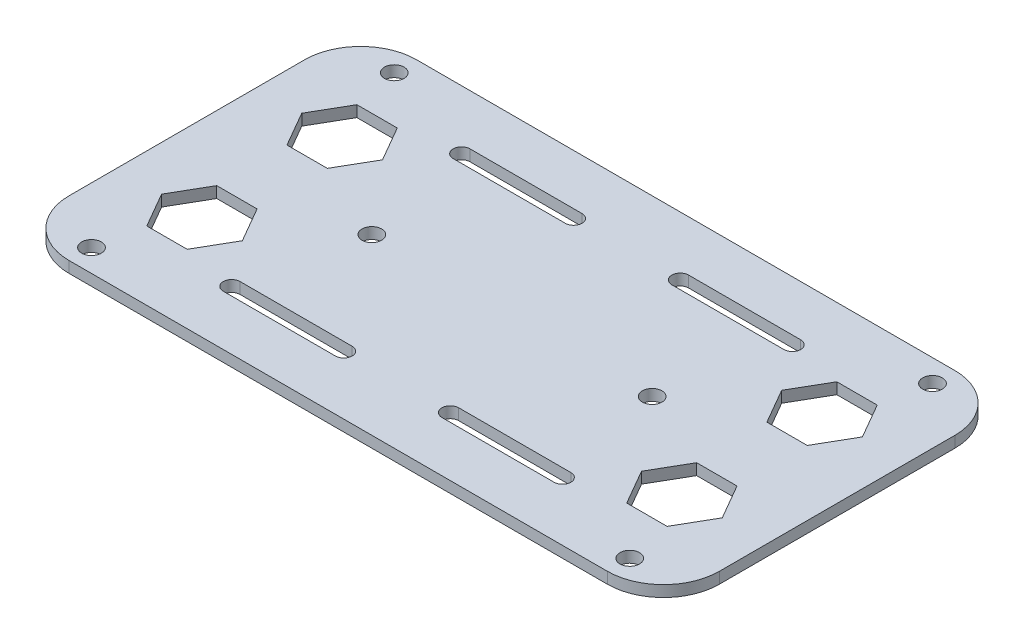
SolidWorks part; units mm, degrees
material "Thornel Mat VMA"
ref_plane "Front Plane" through (0, 0, 0) normal (0, 0, 1) x (1, 0, 0)
ref_plane "Top Plane" through (0, 0, 0) normal (0, 1, 0) x (1, 0, 0)
ref_plane "Right Plane" through (0, 0, 0) normal (1, 0, 0) x (0, 0, -1)
sketch "Sketch1" plane through (0, 0, 0) normal (0, 1, 0) x (1, 0, 0)
  line L1 (-58, 31) -> (58, 31)
  line L2 (-58, 31) -> (-58, -31)
  line L3 (-58, -31) -> (58, -31)
  line L4 (58, 31) -> (58, -31)
  line L5 (-58, 31) -> (58, -31) construction
  line L6 (-58, -31) -> (58, 31) construction
  point P0 (0, 0)
  dimension "D1" = 62
  dimension "D2" = 116
extrude "Boss-Extrude1" add sketch "Sketch1" along normal blind 2
sketch "Sketch2" plane through (0, 2, 0) normal (0, 1, 0) x (1, 0, 0)
  circle A0 centre (-48, 27) radius 1.75
  circle A1 centre (48, 27) radius 1.75
  circle A2 centre (48, -27) radius 1.75
  circle A3 centre (-48, -27) radius 1.75
  dimension "D1" = 3.5
  dimension "D2" = 48
  dimension "D3" = 27
  dimension "D4" = 96
  dimension "D5" = 54
extrude "Cut-Extrude1" cut sketch "Sketch2" against normal blind 2
sketch "Sketch3" plane through (0, 2, 0) normal (0, 1, 0) x (1, 0, 0)
  line L0 (9.5, -20.5) -> (29.5, -20.5) construction
  line L1 (9.5, -19) -> (29.5, -19)
  line L2 (9.5, -22) -> (29.5, -22)
  line L3 (-58, -31) -> (58, -31) construction
  line L4 (-9.5, -20.5) -> (-29.5, -20.5) construction
  line L5 (-9.5, -22) -> (-29.5, -22)
  line L6 (-9.5, -19) -> (-29.5, -19)
  line L7 (-29.5, 20.5) -> (-9.5, 20.5) construction
  line L8 (-29.5, 22) -> (-9.5, 22)
  line L9 (-29.5, 19) -> (-9.5, 19)
  line L10 (9.5, 20.5) -> (29.5, 20.5) construction
  line L11 (9.5, 22) -> (29.5, 22)
  line L12 (9.5, 19) -> (29.5, 19)
  line L13 (58, 31) -> (-58, 31) construction
  line L27 (-35.6, 12.5) -> (-39.2, 18.7354)
  line L28 (-39.2, 18.7354) -> (-46.4, 18.7354)
  line L29 (-46.4, 18.7354) -> (-50, 12.5)
  line L30 (-50, 12.5) -> (-46.4, 6.2646)
  line L31 (-46.4, 6.2646) -> (-39.2, 6.2646)
  line L32 (-39.2, 6.2646) -> (-35.6, 12.5)
  line L33 (-35.6, -12.5) -> (-39.2, -6.2646)
  line L34 (-39.2, -6.2646) -> (-46.4, -6.2646)
  line L35 (-46.4, -6.2646) -> (-50, -12.5)
  line L36 (-50, -12.5) -> (-46.4, -18.7354)
  line L37 (-46.4, -18.7354) -> (-39.2, -18.7354)
  line L38 (-39.2, -18.7354) -> (-35.6, -12.5)
  line L39 (50, 12.5) -> (46.4, 18.7354)
  line L40 (46.4, 18.7354) -> (39.2, 18.7354)
  line L41 (39.2, 18.7354) -> (35.6, 12.5)
  line L42 (35.6, 12.5) -> (39.2, 6.2646)
  line L43 (39.2, 6.2646) -> (46.4, 6.2646)
  line L44 (46.4, 6.2646) -> (50, 12.5)
  line L45 (50, -12.5) -> (46.4, -6.2646)
  line L46 (46.4, -6.2646) -> (39.2, -6.2646)
  line L47 (39.2, -6.2646) -> (35.6, -12.5)
  line L48 (35.6, -12.5) -> (39.2, -18.7354)
  line L49 (39.2, -18.7354) -> (46.4, -18.7354)
  line L50 (46.4, -18.7354) -> (50, -12.5)
  circle A0 centre (25, 0) radius 1.75
  circle A1 centre (-25, 0) radius 1.75
  arc A2 (9.5, -19) -> (9.5, -22) centre (9.5, -20.5) ccw
  arc A3 (29.5, -22) -> (29.5, -19) centre (29.5, -20.5) ccw
  arc A4 (-9.5, -22) -> (-9.5, -19) centre (-9.5, -20.5) ccw
  arc A5 (-29.5, -19) -> (-29.5, -22) centre (-29.5, -20.5) ccw
  arc A6 (-29.5, 22) -> (-29.5, 19) centre (-29.5, 20.5) ccw
  arc A7 (-9.5, 19) -> (-9.5, 22) centre (-9.5, 20.5) ccw
  arc A8 (9.5, 22) -> (9.5, 19) centre (9.5, 20.5) ccw
  arc A9 (29.5, 19) -> (29.5, 22) centre (29.5, 20.5) ccw
  circle A10 centre (-42.8, 12.5) radius 6.2354 construction
  circle A11 centre (-42.8, -12.5) radius 6.2354 construction
  circle A12 centre (42.8, 12.5) radius 6.2354 construction
  circle A13 centre (42.8, -12.5) radius 6.2354 construction
  point P4 (19.5, -20.5)
  point P12 (-19.5, -20.5)
  point P21 (-19.5, 20.5)
  point P26 (19.5, 20.5)
  dimension "D1" = 3.5
  dimension "D2" = 25
  dimension "D4" = 1.5
  dimension "D7" = 39
  dimension "D10" = 9
  dimension "D3" = 50
  dimension "D5" = 29.5
  dimension "D6" = 9
  dimension "D8" = 59
  dimension "D9" = 19
  dimension "D11" = 19
  dimension "D12" = 21.225
  dimension "D13" = 20
  dimension "D14" = 7.2
  dimension "D15" = 100
  dimension "D16" = 25
  dimension "D17" = 12.5
  dimension "D18" = 50
  dimension "D20" = 25
  dimension "D21" = 25
  dimension "D22" = 12.5292
extrude "Cut-Extrude2" cut sketch "Sketch3" against normal blind 2
fillet "Fillet2" radius 10 4 edges at (58, 1, -31) (58, 1, 31) (-58, 1, 31) (-58, 1, -31)
